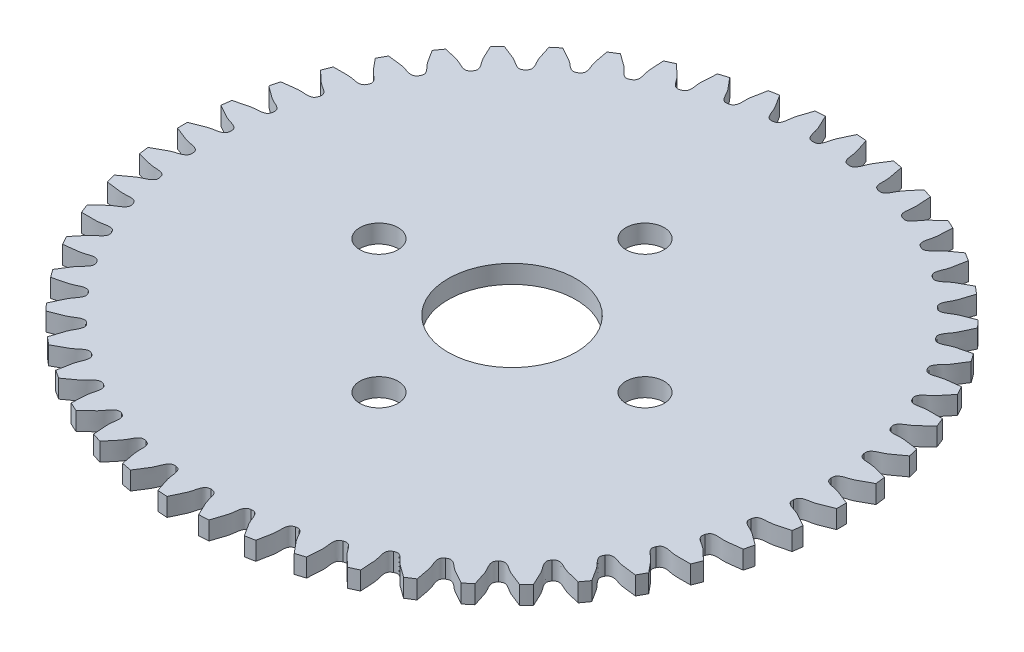
SolidWorks part; units mm, degrees
ref_plane "Front" through (0, 0, 0) normal (0, 0, 1) x (1, 0, 0)
ref_plane "Top" through (0, 0, 0) normal (0, 1, 0) x (1, 0, 0)
ref_plane "Right" through (0, 0, 0) normal (1, 0, 0) x (0, 0, -1)
sketch "Sketch1" plane through (0, 0, 0) normal (0, 1, 0) x (1, 0, 0)
  arc A0 (-11.3167, -17.258) -> (-10.7971, -17.5878) centre (0, 0) ccw
  arc A1 (-13.3905, -15.7035) -> (-12.9163, -16.0959) centre (0, 0) ccw
  arc A2 (-15.2531, -13.9014) -> (-14.8318, -14.3501) centre (0, 0) ccw
  arc A3 (-16.8751, -11.8801) -> (-16.5133, -12.378) centre (0, 0) ccw
  arc A4 (-18.231, -9.6714) -> (-17.9345, -10.2108) centre (0, 0) ccw
  arc A5 (-19.2994, -7.3102) -> (-19.0728, -7.8825) centre (0, 0) ccw
  arc A7 (-20.0634, -4.8337) -> (-19.9104, -5.4298) centre (0, 0) ccw
  arc A8 (-20.5111, -2.281) -> (-20.4339, -2.8916) centre (0, 0) ccw
  arc A9 (-20.6352, 0.3077) -> (-20.6352, -0.3077) centre (0, 0) ccw
  arc A10 (-20.4339, 2.8916) -> (-20.5111, 2.281) centre (0, 0) ccw
  arc A11 (-19.9104, 5.4298) -> (-20.0634, 4.8337) centre (0, 0) ccw
  arc A12 (-19.0728, 7.8825) -> (-19.2994, 7.3102) centre (0, 0) ccw
  arc A13 (-17.9345, 10.2108) -> (-18.231, 9.6714) centre (0, 0) ccw
  arc A14 (-16.5133, 12.378) -> (-16.8751, 11.8801) centre (0, 0) ccw
  arc A15 (-14.8318, 14.3501) -> (-15.2531, 13.9014) centre (0, 0) ccw
  arc A16 (-12.9163, 16.0959) -> (-13.3905, 15.7035) centre (0, 0) ccw
  arc A17 (-10.7971, 17.5878) -> (-11.3167, 17.258) centre (0, 0) ccw
  arc A18 (-8.5076, 18.8023) -> (-9.0645, 18.5403) centre (0, 0) ccw
  arc A19 (-6.084, 19.7203) -> (-6.6693, 19.5302) centre (0, 0) ccw
  arc A20 (-3.5644, 20.3274) -> (-4.1689, 20.212) centre (0, 0) ccw
  arc A21 (-0.9886, 20.6138) -> (-1.6028, 20.5752) centre (0, 0) ccw
  arc A22 (1.6028, 20.5752) -> (0.9886, 20.6138) centre (0, 0) ccw
  arc A23 (4.1689, 20.212) -> (3.5644, 20.3274) centre (0, 0) ccw
  arc A24 (6.6693, 19.5302) -> (6.084, 19.7203) centre (0, 0) ccw
  arc A25 (9.0645, 18.5403) -> (8.5076, 18.8023) centre (0, 0) ccw
  arc A26 (11.3167, 17.258) -> (10.7971, 17.5878) centre (0, 0) ccw
  arc A27 (13.3905, 15.7035) -> (12.9163, 16.0959) centre (0, 0) ccw
  arc A28 (15.2531, 13.9014) -> (14.8318, 14.3501) centre (0, 0) ccw
  arc A29 (16.8751, 11.8801) -> (16.5133, 12.378) centre (0, 0) ccw
  arc A30 (18.231, 9.6714) -> (17.9345, 10.2108) centre (0, 0) ccw
  arc A31 (19.2994, 7.3102) -> (19.0728, 7.8825) centre (0, 0) ccw
  arc A32 (20.0634, 4.8337) -> (19.9104, 5.4298) centre (0, 0) ccw
  arc A33 (20.5111, 2.281) -> (20.4339, 2.8916) centre (0, 0) ccw
  arc A34 (20.6352, -0.3077) -> (20.6352, 0.3077) centre (0, 0) ccw
  arc A35 (20.4339, -2.8916) -> (20.5111, -2.281) centre (0, 0) ccw
  arc A36 (-9.0645, -18.5403) -> (-8.5076, -18.8023) centre (0, 0) ccw
  arc A37 (19.9104, -5.4298) -> (20.0634, -4.8337) centre (0, 0) ccw
  arc A38 (19.0728, -7.8825) -> (19.2994, -7.3102) centre (0, 0) ccw
  arc A39 (17.9345, -10.2108) -> (18.231, -9.6714) centre (0, 0) ccw
  arc A40 (16.5133, -12.378) -> (16.8751, -11.8801) centre (0, 0) ccw
  arc A41 (14.8318, -14.3501) -> (15.2531, -13.9014) centre (0, 0) ccw
  arc A42 (12.9163, -16.0959) -> (13.3905, -15.7035) centre (0, 0) ccw
  arc A43 (10.7971, -17.5878) -> (11.3167, -17.258) centre (0, 0) ccw
  arc A44 (8.5076, -18.8023) -> (9.0645, -18.5403) centre (0, 0) ccw
  arc A45 (6.084, -19.7203) -> (6.6693, -19.5302) centre (0, 0) ccw
  arc A46 (3.5644, -20.3274) -> (4.1689, -20.212) centre (0, 0) ccw
  arc A47 (0.9886, -20.6138) -> (1.6028, -20.5752) centre (0, 0) ccw
  arc A48 (-1.6028, -20.5752) -> (-0.9886, -20.6138) centre (0, 0) ccw
  arc A49 (-4.1689, -20.212) -> (-3.5644, -20.3274) centre (0, 0) ccw
  arc A50 (-6.6693, -19.5302) -> (-6.084, -19.7203) centre (0, 0) ccw
  circle A51 centre (0, 0) radius 4
  circle A52 centre (-8.331, 0) radius 1.2
  circle A53 centre (0, 8.331) radius 1.2
  circle A54 centre (8.331, 0) radius 1.2
  circle A55 centre (0, -8.331) radius 1.2
  spline S0 degree 3 poles (-10.7971, -17.5878) (-10.6686, -17.4999) (-10.3251, -17.2651) (-9.873, -16.9278) (-9.5768, -16.5504) (-9.2878, -16.4134) (-9.1437, -16.4793) (-9.0765, -16.51) knots 0 0 0 0 0.220154 0.588354 0.785743 0.900027 1 1 1 1
  spline S1 degree 3 poles (-11.3167, -17.258) (-11.2919, -17.1043) (-11.2257, -16.6936) (-11.113, -16.1408) (-10.8977, -15.7122) (-10.8967, -15.3923) (-11.0177, -15.29) (-11.0741, -15.2422) knots 0 0 0 0 0.220154 0.588354 0.785743 0.900027 1 1 1 1
  spline S2 degree 3 poles (-12.9163, -16.0959) (-12.7778, -16.0248) (-12.4076, -15.8349) (-11.9168, -15.5569) (-11.5756, -15.2196) (-11.2717, -15.1199) (-11.137, -15.2033) (-11.0741, -15.2422) knots 0 0 0 0 0.220154 0.588354 0.785743 0.900027 1 1 1 1
  spline S3 degree 3 poles (-13.3905, -15.7035) (-13.3466, -15.5542) (-13.2294, -15.155) (-13.0483, -14.6207) (-12.781, -14.2224) (-12.74, -13.9052) (-12.8472, -13.7885) (-12.8972, -13.7341) knots 0 0 0 0 0.220154 0.588354 0.785743 0.900027 1 1 1 1
  spline S4 degree 3 poles (-14.8318, -14.3501) (-14.6854, -14.297) (-14.2944, -14.1549) (-13.7726, -13.9406) (-13.3918, -13.6488) (-13.0779, -13.5879) (-12.9547, -13.6876) (-12.8972, -13.7341) knots 0 0 0 0 0.220154 0.588354 0.785743 0.900027 1 1 1 1
  spline S5 degree 3 poles (-15.2531, -13.9014) (-15.1909, -13.7587) (-15.0246, -13.3774) (-14.7779, -12.8701) (-14.4627, -12.5084) (-14.3823, -12.1989) (-14.474, -12.0696) (-14.5168, -12.0094) knots 0 0 0 0 0.220154 0.588354 0.785743 0.900027 1 1 1 1
  spline S6 degree 3 poles (-16.5133, -12.378) (-16.3615, -12.3436) (-15.9558, -12.2517) (-15.4112, -12.1045) (-14.9969, -11.8627) (-14.6778, -11.8417) (-14.568, -11.956) (-14.5168, -12.0094) knots 0 0 0 0 0.220154 0.588354 0.785743 0.900027 1 1 1 1
  spline S7 degree 3 poles (-16.8751, -11.8801) (-16.7955, -11.7463) (-16.5827, -11.3889) (-16.2744, -10.9164) (-15.9164, -10.5971) (-15.7978, -10.3001) (-15.8726, -10.1604) (-15.9075, -10.0952) knots 0 0 0 0 0.220154 0.588354 0.785743 0.900027 1 1 1 1
  spline S8 degree 3 poles (-17.9345, -10.2108) (-17.7796, -10.1957) (-17.3655, -10.1553) (-16.8068, -10.0776) (-16.3654, -9.8896) (-16.0462, -9.9087) (-15.9516, -10.0359) (-15.9075, -10.0952) knots 0 0 0 0 0.220154 0.588354 0.785743 0.900027 1 1 1 1
  spline S9 degree 3 poles (-18.231, -9.6714) (-18.1353, -9.5487) (-17.8794, -9.2207) (-17.5143, -8.7906) (-17.1191, -8.5187) (-16.9642, -8.2389) (-17.0209, -8.0909) (-17.0473, -8.0219) knots 0 0 0 0 0.220154 0.588354 0.785743 0.900027 1 1 1 1
  spline S10 degree 3 poles (-19.0728, -7.8825) (-18.9172, -7.8869) (-18.5014, -7.8988) (-17.9373, -7.8916) (-17.4759, -7.7605) (-17.1615, -7.8195) (-17.0837, -7.9575) (-17.0473, -8.0219) knots 0 0 0 0 0.220154 0.588354 0.785743 0.900027 1 1 1 1
  spline S11 degree 3 poles (-19.2994, -7.3102) (-19.189, -7.2004) (-18.894, -6.9071) (-18.4779, -6.5262) (-18.0518, -6.3059) (-17.863, -6.0477) (-17.9007, -5.8938) (-17.9183, -5.822) knots 0 0 0 0 0.220154 0.588354 0.785743 0.900027 1 1 1 1
  spline S12 degree 3 poles (-19.9104, -5.4298) (-19.7566, -5.4538) (-19.3455, -5.5177) (-18.785, -5.5813) (-18.3107, -5.509) (-18.0062, -5.6069) (-17.9463, -5.7536) (-17.9183, -5.822) knots 0 0 0 0 0.220154 0.588354 0.785743 0.900027 1 1 1 1
  spline S13 degree 3 poles (-20.0634, -4.8337) (-19.9402, -4.7386) (-19.6107, -4.4846) (-19.1502, -4.1588) (-18.6998, -3.9937) (-18.4801, -3.7612) (-18.4983, -3.6038) (-18.5067, -3.5303) knots 0 0 0 0 0.220154 0.588354 0.785743 0.900027 1 1 1 1
  spline S14 degree 3 poles (-20.4339, -2.8916) (-20.2843, -2.9346) (-19.8845, -3.0495) (-19.3364, -3.1829) (-18.8568, -3.1706) (-18.567, -3.3059) (-18.5259, -3.4589) (-18.5067, -3.5303) knots 0 0 0 0 0.220154 0.588354 0.785743 0.900027 1 1 1 1
  spline S15 degree 3 poles (-20.5111, -2.281) (-20.3768, -2.2021) (-20.0182, -1.9913) (-19.5204, -1.7259) (-19.0529, -1.6185) (-18.8058, -1.4154) (-18.8041, -1.2569) (-18.8033, -1.183) knots 0 0 0 0 0.220154 0.588354 0.785743 0.900027 1 1 1 1
  spline S16 degree 3 poles (-20.6352, -0.3077) (-20.4922, -0.3692) (-20.1099, -0.5333) (-19.5828, -0.7343) (-19.1055, -0.7822) (-18.8349, -0.9528) (-18.8133, -1.1098) (-18.8033, -1.183) knots 0 0 0 0 0.220154 0.588354 0.785743 0.900027 1 1 1 1
  spline S17 degree 3 poles (-20.6352, 0.3077) (-20.4922, 0.3692) (-20.1099, 0.5333) (-19.5828, 0.7343) (-19.1055, 0.7822) (-18.8349, 0.9528) (-18.8133, 1.1098) (-18.8033, 1.183) knots 0 0 0 0 0.220154 0.588354 0.785743 0.900027 1 1 1 1
  spline S18 degree 3 poles (-20.5111, 2.281) (-20.3768, 2.2021) (-20.0182, 1.9913) (-19.5204, 1.7259) (-19.0529, 1.6185) (-18.8058, 1.4154) (-18.8041, 1.2569) (-18.8033, 1.183) knots 0 0 0 0 0.220154 0.588354 0.785743 0.900027 1 1 1 1
  spline S19 degree 3 poles (-20.4339, 2.8916) (-20.2843, 2.9346) (-19.8845, 3.0495) (-19.3364, 3.1829) (-18.8568, 3.1706) (-18.567, 3.3059) (-18.5259, 3.4589) (-18.5067, 3.5303) knots 0 0 0 0 0.220154 0.588354 0.785743 0.900027 1 1 1 1
  spline S20 degree 3 poles (-20.0634, 4.8337) (-19.9402, 4.7386) (-19.6107, 4.4846) (-19.1502, 4.1588) (-18.6998, 3.9937) (-18.4801, 3.7612) (-18.4983, 3.6038) (-18.5067, 3.5303) knots 0 0 0 0 0.220154 0.588354 0.785743 0.900027 1 1 1 1
  spline S21 degree 3 poles (-19.9104, 5.4298) (-19.7566, 5.4538) (-19.3455, 5.5177) (-18.785, 5.5813) (-18.3107, 5.509) (-18.0062, 5.6069) (-17.9463, 5.7536) (-17.9183, 5.822) knots 0 0 0 0 0.220154 0.588354 0.785743 0.900027 1 1 1 1
  spline S22 degree 3 poles (-19.2994, 7.3102) (-19.189, 7.2004) (-18.894, 6.9071) (-18.4779, 6.5262) (-18.0518, 6.3059) (-17.863, 6.0477) (-17.9007, 5.8938) (-17.9183, 5.822) knots 0 0 0 0 0.220154 0.588354 0.785743 0.900027 1 1 1 1
  spline S23 degree 3 poles (-19.0728, 7.8825) (-18.9172, 7.8869) (-18.5014, 7.8988) (-17.9373, 7.8916) (-17.4759, 7.7605) (-17.1615, 7.8195) (-17.0837, 7.9575) (-17.0473, 8.0219) knots 0 0 0 0 0.220154 0.588354 0.785743 0.900027 1 1 1 1
  spline S24 degree 3 poles (-18.231, 9.6714) (-18.1353, 9.5487) (-17.8794, 9.2207) (-17.5143, 8.7906) (-17.1191, 8.5187) (-16.9642, 8.2389) (-17.0209, 8.0909) (-17.0473, 8.0219) knots 0 0 0 0 0.220154 0.588354 0.785743 0.900027 1 1 1 1
  spline S25 degree 3 poles (-17.9345, 10.2108) (-17.7796, 10.1957) (-17.3655, 10.1553) (-16.8068, 10.0776) (-16.3654, 9.8896) (-16.0462, 9.9087) (-15.9516, 10.0359) (-15.9075, 10.0952) knots 0 0 0 0 0.220154 0.588354 0.785743 0.900027 1 1 1 1
  spline S26 degree 3 poles (-16.8751, 11.8801) (-16.7955, 11.7463) (-16.5827, 11.3889) (-16.2744, 10.9164) (-15.9164, 10.5971) (-15.7978, 10.3001) (-15.8726, 10.1604) (-15.9075, 10.0952) knots 0 0 0 0 0.220154 0.588354 0.785743 0.900027 1 1 1 1
  spline S27 degree 3 poles (-16.5133, 12.378) (-16.3615, 12.3436) (-15.9558, 12.2517) (-15.4112, 12.1045) (-14.9969, 11.8627) (-14.6778, 11.8417) (-14.568, 11.956) (-14.5168, 12.0094) knots 0 0 0 0 0.220154 0.588354 0.785743 0.900027 1 1 1 1
  spline S28 degree 3 poles (-15.2531, 13.9014) (-15.1909, 13.7587) (-15.0246, 13.3774) (-14.7779, 12.8701) (-14.4627, 12.5084) (-14.3823, 12.1989) (-14.474, 12.0696) (-14.5168, 12.0094) knots 0 0 0 0 0.220154 0.588354 0.785743 0.900027 1 1 1 1
  spline S29 degree 3 poles (-14.8318, 14.3501) (-14.6854, 14.297) (-14.2944, 14.1549) (-13.7726, 13.9406) (-13.3918, 13.6488) (-13.0779, 13.5879) (-12.9547, 13.6876) (-12.8972, 13.7341) knots 0 0 0 0 0.220154 0.588354 0.785743 0.900027 1 1 1 1
  spline S30 degree 3 poles (-13.3905, 15.7035) (-13.3466, 15.5542) (-13.2294, 15.155) (-13.0483, 14.6207) (-12.781, 14.2224) (-12.74, 13.9052) (-12.8472, 13.7885) (-12.8972, 13.7341) knots 0 0 0 0 0.220154 0.588354 0.785743 0.900027 1 1 1 1
  spline S31 degree 3 poles (-12.9163, 16.0959) (-12.7778, 16.0248) (-12.4076, 15.8349) (-11.9168, 15.5569) (-11.5756, 15.2196) (-11.2717, 15.1199) (-11.137, 15.2033) (-11.0741, 15.2422) knots 0 0 0 0 0.220154 0.588354 0.785743 0.900027 1 1 1 1
  spline S32 degree 3 poles (-11.3167, 17.258) (-11.2919, 17.1043) (-11.2257, 16.6936) (-11.113, 16.1408) (-10.8977, 15.7122) (-10.8967, 15.3923) (-11.0177, 15.29) (-11.0741, 15.2422) knots 0 0 0 0 0.220154 0.588354 0.785743 0.900027 1 1 1 1
  spline S33 degree 3 poles (-10.7971, 17.5878) (-10.6686, 17.4999) (-10.3251, 17.2651) (-9.873, 16.9278) (-9.5768, 16.5504) (-9.2878, 16.4134) (-9.1437, 16.4793) (-9.0765, 16.51) knots 0 0 0 0 0.220154 0.588354 0.785743 0.900027 1 1 1 1
  spline S34 degree 3 poles (-9.0645, 18.5403) (-9.0592, 18.3847) (-9.0449, 17.9689) (-9.0024, 17.4064) (-8.8425, 16.9541) (-8.8816, 16.6367) (-9.0145, 16.5503) (-9.0765, 16.51) knots 0 0 0 0 0.220154 0.588354 0.785743 0.900027 1 1 1 1
  spline S35 degree 3 poles (-8.5076, 18.8023) (-8.3911, 18.699) (-8.0798, 18.423) (-7.6735, 18.0317) (-7.4269, 17.6202) (-7.1574, 17.448) (-7.0062, 17.4953) (-6.9356, 17.5174) knots 0 0 0 0 0.220154 0.588354 0.785743 0.900027 1 1 1 1
  spline S36 degree 3 poles (-6.6693, 19.5302) (-6.6835, 19.3751) (-6.7215, 18.9609) (-6.7498, 18.3974) (-6.6478, 17.9287) (-6.7265, 17.6187) (-6.8691, 17.5496) (-6.9356, 17.5174) knots 0 0 0 0 0.220154 0.588354 0.785743 0.900027 1 1 1 1
  spline S37 degree 3 poles (-6.084, 19.7203) (-5.9813, 19.6033) (-5.7071, 19.2904) (-5.3531, 18.8513) (-5.16, 18.4121) (-4.9142, 18.2075) (-4.7582, 18.2355) (-4.6854, 18.2485) knots 0 0 0 0 0.220154 0.588354 0.785743 0.900027 1 1 1 1
  spline S38 degree 3 poles (-4.1689, 20.212) (-4.2025, 20.06) (-4.2921, 19.6538) (-4.3907, 19.0983) (-4.3484, 18.6205) (-4.4652, 18.3228) (-4.6154, 18.2722) (-4.6854, 18.2485) knots 0 0 0 0 0.220154 0.588354 0.785743 0.900027 1 1 1 1
  spline S39 degree 3 poles (-3.5644, 20.3274) (-3.4772, 20.1984) (-3.2444, 19.8536) (-2.9482, 19.3735) (-2.8117, 18.9136) (-2.5934, 18.6798) (-2.4352, 18.6881) (-2.3613, 18.6919) knots 0 0 0 0 0.220154 0.588354 0.785743 0.900027 1 1 1 1
  spline S40 degree 3 poles (-1.6028, 20.5752) (-1.6551, 20.4285) (-1.795, 20.0367) (-1.9625, 19.4981) (-1.9803, 19.0187) (-2.1335, 18.7379) (-2.2889, 18.7065) (-2.3613, 18.6919) knots 0 0 0 0 0.220154 0.588354 0.785743 0.900027 1 1 1 1
  spline S41 degree 3 poles (-0.9886, 20.6138) (-0.9183, 20.4749) (-0.7305, 20.1037) (-0.4968, 19.5903) (-0.419, 19.1169) (-0.2318, 18.8576) (-0.0737, 18.8459) (0, 18.8405) knots 0 0 0 0 0.220154 0.588354 0.785743 0.900027 1 1 1 1
  spline S42 degree 3 poles (0.9886, 20.6138) (0.9183, 20.4749) (0.7305, 20.1037) (0.4968, 19.5903) (0.419, 19.1169) (0.2318, 18.8576) (0.0737, 18.8459) (0, 18.8405) knots 0 0 0 0 0.220154 0.588354 0.785743 0.900027 1 1 1 1
  spline S43 degree 3 poles (1.6028, 20.5752) (1.6551, 20.4285) (1.795, 20.0367) (1.9625, 19.4981) (1.9803, 19.0187) (2.1335, 18.7379) (2.2889, 18.7065) (2.3613, 18.6919) knots 0 0 0 0 0.220154 0.588354 0.785743 0.900027 1 1 1 1
  spline S44 degree 3 poles (3.5644, 20.3274) (3.4772, 20.1984) (3.2444, 19.8536) (2.9482, 19.3735) (2.8117, 18.9136) (2.5934, 18.6798) (2.4352, 18.6881) (2.3613, 18.6919) knots 0 0 0 0 0.220154 0.588354 0.785743 0.900027 1 1 1 1
  spline S45 degree 3 poles (4.1689, 20.212) (4.2025, 20.06) (4.2921, 19.6538) (4.3907, 19.0983) (4.3484, 18.6205) (4.4652, 18.3228) (4.6154, 18.2722) (4.6854, 18.2485) knots 0 0 0 0 0.220154 0.588354 0.785743 0.900027 1 1 1 1
  spline S46 degree 3 poles (6.084, 19.7203) (5.9813, 19.6033) (5.7071, 19.2904) (5.3531, 18.8513) (5.16, 18.4121) (4.9142, 18.2075) (4.7582, 18.2355) (4.6854, 18.2485) knots 0 0 0 0 0.220154 0.588354 0.785743 0.900027 1 1 1 1
  spline S47 degree 3 poles (6.6693, 19.5302) (6.6835, 19.3751) (6.7215, 18.9609) (6.7498, 18.3974) (6.6478, 17.9287) (6.7265, 17.6187) (6.8691, 17.5496) (6.9356, 17.5174) knots 0 0 0 0 0.220154 0.588354 0.785743 0.900027 1 1 1 1
  spline S48 degree 3 poles (8.5076, 18.8023) (8.3911, 18.699) (8.0798, 18.423) (7.6735, 18.0317) (7.4269, 17.6202) (7.1574, 17.448) (7.0062, 17.4953) (6.9356, 17.5174) knots 0 0 0 0 0.220154 0.588354 0.785743 0.900027 1 1 1 1
  spline S49 degree 3 poles (9.0645, 18.5403) (9.0592, 18.3847) (9.0449, 17.9689) (9.0024, 17.4064) (8.8425, 16.9541) (8.8816, 16.6367) (9.0145, 16.5503) (9.0765, 16.51) knots 0 0 0 0 0.220154 0.588354 0.785743 0.900027 1 1 1 1
  spline S50 degree 3 poles (10.7971, 17.5878) (10.6686, 17.4999) (10.3251, 17.2651) (9.873, 16.9278) (9.5768, 16.5504) (9.2878, 16.4134) (9.1437, 16.4793) (9.0765, 16.51) knots 0 0 0 0 0.220154 0.588354 0.785743 0.900027 1 1 1 1
  spline S51 degree 3 poles (11.3167, 17.258) (11.2919, 17.1043) (11.2257, 16.6936) (11.113, 16.1408) (10.8977, 15.7122) (10.8967, 15.3923) (11.0177, 15.29) (11.0741, 15.2422) knots 0 0 0 0 0.220154 0.588354 0.785743 0.900027 1 1 1 1
  spline S52 degree 3 poles (12.9163, 16.0959) (12.7778, 16.0248) (12.4076, 15.8349) (11.9168, 15.5569) (11.5756, 15.2196) (11.2717, 15.1199) (11.137, 15.2033) (11.0741, 15.2422) knots 0 0 0 0 0.220154 0.588354 0.785743 0.900027 1 1 1 1
  spline S53 degree 3 poles (13.3905, 15.7035) (13.3466, 15.5542) (13.2294, 15.155) (13.0483, 14.6207) (12.781, 14.2224) (12.74, 13.9052) (12.8472, 13.7885) (12.8972, 13.7341) knots 0 0 0 0 0.220154 0.588354 0.785743 0.900027 1 1 1 1
  spline S54 degree 3 poles (14.8318, 14.3501) (14.6854, 14.297) (14.2944, 14.1549) (13.7726, 13.9406) (13.3918, 13.6488) (13.0779, 13.5879) (12.9547, 13.6876) (12.8972, 13.7341) knots 0 0 0 0 0.220154 0.588354 0.785743 0.900027 1 1 1 1
  spline S55 degree 3 poles (15.2531, 13.9014) (15.1909, 13.7587) (15.0246, 13.3774) (14.7779, 12.8701) (14.4627, 12.5084) (14.3823, 12.1989) (14.474, 12.0696) (14.5168, 12.0094) knots 0 0 0 0 0.220154 0.588354 0.785743 0.900027 1 1 1 1
  spline S56 degree 3 poles (16.5133, 12.378) (16.3615, 12.3436) (15.9558, 12.2517) (15.4112, 12.1045) (14.9969, 11.8627) (14.6778, 11.8417) (14.568, 11.956) (14.5168, 12.0094) knots 0 0 0 0 0.220154 0.588354 0.785743 0.900027 1 1 1 1
  spline S57 degree 3 poles (16.8751, 11.8801) (16.7955, 11.7463) (16.5827, 11.3889) (16.2744, 10.9164) (15.9164, 10.5971) (15.7978, 10.3001) (15.8726, 10.1604) (15.9075, 10.0952) knots 0 0 0 0 0.220154 0.588354 0.785743 0.900027 1 1 1 1
  spline S58 degree 3 poles (17.9345, 10.2108) (17.7796, 10.1957) (17.3655, 10.1553) (16.8068, 10.0776) (16.3654, 9.8896) (16.0462, 9.9087) (15.9516, 10.0359) (15.9075, 10.0952) knots 0 0 0 0 0.220154 0.588354 0.785743 0.900027 1 1 1 1
  spline S59 degree 3 poles (18.231, 9.6714) (18.1353, 9.5487) (17.8794, 9.2207) (17.5143, 8.7906) (17.1191, 8.5187) (16.9642, 8.2389) (17.0209, 8.0909) (17.0473, 8.0219) knots 0 0 0 0 0.220154 0.588354 0.785743 0.900027 1 1 1 1
  spline S60 degree 3 poles (19.0728, 7.8825) (18.9172, 7.8869) (18.5014, 7.8988) (17.9373, 7.8916) (17.4759, 7.7605) (17.1615, 7.8195) (17.0837, 7.9575) (17.0473, 8.0219) knots 0 0 0 0 0.220154 0.588354 0.785743 0.900027 1 1 1 1
  spline S61 degree 3 poles (19.2994, 7.3102) (19.189, 7.2004) (18.894, 6.9071) (18.4779, 6.5262) (18.0518, 6.3059) (17.863, 6.0477) (17.9007, 5.8938) (17.9183, 5.822) knots 0 0 0 0 0.220154 0.588354 0.785743 0.900027 1 1 1 1
  spline S62 degree 3 poles (19.9104, 5.4298) (19.7566, 5.4538) (19.3455, 5.5177) (18.785, 5.5813) (18.3107, 5.509) (18.0062, 5.6069) (17.9463, 5.7536) (17.9183, 5.822) knots 0 0 0 0 0.220154 0.588354 0.785743 0.900027 1 1 1 1
  spline S63 degree 3 poles (20.0634, 4.8337) (19.9402, 4.7386) (19.6107, 4.4846) (19.1502, 4.1588) (18.6998, 3.9937) (18.4801, 3.7612) (18.4983, 3.6038) (18.5067, 3.5303) knots 0 0 0 0 0.220154 0.588354 0.785743 0.900027 1 1 1 1
  spline S64 degree 3 poles (-8.5076, -18.8023) (-8.3911, -18.699) (-8.0798, -18.423) (-7.6735, -18.0317) (-7.4269, -17.6202) (-7.1574, -17.448) (-7.0062, -17.4953) (-6.9356, -17.5174) knots 0 0 0 0 0.220154 0.588354 0.785743 0.900027 1 1 1 1
  spline S65 degree 3 poles (-9.0645, -18.5403) (-9.0592, -18.3847) (-9.0449, -17.9689) (-9.0024, -17.4064) (-8.8425, -16.9541) (-8.8816, -16.6367) (-9.0145, -16.5503) (-9.0765, -16.51) knots 0 0 0 0 0.220154 0.588354 0.785743 0.900027 1 1 1 1
  spline S66 degree 3 poles (20.4339, 2.8916) (20.2843, 2.9346) (19.8845, 3.0495) (19.3364, 3.1829) (18.8568, 3.1706) (18.567, 3.3059) (18.5259, 3.4589) (18.5067, 3.5303) knots 0 0 0 0 0.220154 0.588354 0.785743 0.900027 1 1 1 1
  spline S67 degree 3 poles (20.5111, 2.281) (20.3768, 2.2021) (20.0182, 1.9913) (19.5204, 1.7259) (19.0529, 1.6185) (18.8058, 1.4154) (18.8041, 1.2569) (18.8033, 1.183) knots 0 0 0 0 0.220154 0.588354 0.785743 0.900027 1 1 1 1
  spline S68 degree 3 poles (20.6352, 0.3077) (20.4922, 0.3692) (20.1099, 0.5333) (19.5828, 0.7343) (19.1055, 0.7822) (18.8349, 0.9528) (18.8133, 1.1098) (18.8033, 1.183) knots 0 0 0 0 0.220154 0.588354 0.785743 0.900027 1 1 1 1
  spline S69 degree 3 poles (20.6352, -0.3077) (20.4922, -0.3692) (20.1099, -0.5333) (19.5828, -0.7343) (19.1055, -0.7822) (18.8349, -0.9528) (18.8133, -1.1098) (18.8033, -1.183) knots 0 0 0 0 0.220154 0.588354 0.785743 0.900027 1 1 1 1
  spline S70 degree 3 poles (20.5111, -2.281) (20.3768, -2.2021) (20.0182, -1.9913) (19.5204, -1.7259) (19.0529, -1.6185) (18.8058, -1.4154) (18.8041, -1.2569) (18.8033, -1.183) knots 0 0 0 0 0.220154 0.588354 0.785743 0.900027 1 1 1 1
  spline S71 degree 3 poles (20.4339, -2.8916) (20.2843, -2.9346) (19.8845, -3.0495) (19.3364, -3.1829) (18.8568, -3.1706) (18.567, -3.3059) (18.5259, -3.4589) (18.5067, -3.5303) knots 0 0 0 0 0.220154 0.588354 0.785743 0.900027 1 1 1 1
  spline S72 degree 3 poles (20.0634, -4.8337) (19.9402, -4.7386) (19.6107, -4.4846) (19.1502, -4.1588) (18.6998, -3.9937) (18.4801, -3.7612) (18.4983, -3.6038) (18.5067, -3.5303) knots 0 0 0 0 0.220154 0.588354 0.785743 0.900027 1 1 1 1
  spline S73 degree 3 poles (19.9104, -5.4298) (19.7566, -5.4538) (19.3455, -5.5177) (18.785, -5.5813) (18.3107, -5.509) (18.0062, -5.6069) (17.9463, -5.7536) (17.9183, -5.822) knots 0 0 0 0 0.220154 0.588354 0.785743 0.900027 1 1 1 1
  spline S74 degree 3 poles (19.2994, -7.3102) (19.189, -7.2004) (18.894, -6.9071) (18.4779, -6.5262) (18.0518, -6.3059) (17.863, -6.0477) (17.9007, -5.8938) (17.9183, -5.822) knots 0 0 0 0 0.220154 0.588354 0.785743 0.900027 1 1 1 1
  spline S75 degree 3 poles (19.0728, -7.8825) (18.9172, -7.8869) (18.5014, -7.8988) (17.9373, -7.8916) (17.4759, -7.7605) (17.1615, -7.8195) (17.0837, -7.9575) (17.0473, -8.0219) knots 0 0 0 0 0.220154 0.588354 0.785743 0.900027 1 1 1 1
  spline S76 degree 3 poles (18.231, -9.6714) (18.1353, -9.5487) (17.8794, -9.2207) (17.5143, -8.7906) (17.1191, -8.5187) (16.9642, -8.2389) (17.0209, -8.0909) (17.0473, -8.0219) knots 0 0 0 0 0.220154 0.588354 0.785743 0.900027 1 1 1 1
  spline S77 degree 3 poles (17.9345, -10.2108) (17.7796, -10.1957) (17.3655, -10.1553) (16.8068, -10.0776) (16.3654, -9.8896) (16.0462, -9.9087) (15.9516, -10.0359) (15.9075, -10.0952) knots 0 0 0 0 0.220154 0.588354 0.785743 0.900027 1 1 1 1
  spline S78 degree 3 poles (16.8751, -11.8801) (16.7955, -11.7463) (16.5827, -11.3889) (16.2744, -10.9164) (15.9164, -10.5971) (15.7978, -10.3001) (15.8726, -10.1604) (15.9075, -10.0952) knots 0 0 0 0 0.220154 0.588354 0.785743 0.900027 1 1 1 1
  spline S79 degree 3 poles (16.5133, -12.378) (16.3615, -12.3436) (15.9558, -12.2517) (15.4112, -12.1045) (14.9969, -11.8627) (14.6778, -11.8417) (14.568, -11.956) (14.5168, -12.0094) knots 0 0 0 0 0.220154 0.588354 0.785743 0.900027 1 1 1 1
  spline S80 degree 3 poles (15.2531, -13.9014) (15.1909, -13.7587) (15.0246, -13.3774) (14.7779, -12.8701) (14.4627, -12.5084) (14.3823, -12.1989) (14.474, -12.0696) (14.5168, -12.0094) knots 0 0 0 0 0.220154 0.588354 0.785743 0.900027 1 1 1 1
  spline S81 degree 3 poles (14.8318, -14.3501) (14.6854, -14.297) (14.2944, -14.1549) (13.7726, -13.9406) (13.3918, -13.6488) (13.0779, -13.5879) (12.9547, -13.6876) (12.8972, -13.7341) knots 0 0 0 0 0.220154 0.588354 0.785743 0.900027 1 1 1 1
  spline S82 degree 3 poles (13.3905, -15.7035) (13.3466, -15.5542) (13.2294, -15.155) (13.0483, -14.6207) (12.781, -14.2224) (12.74, -13.9052) (12.8472, -13.7885) (12.8972, -13.7341) knots 0 0 0 0 0.220154 0.588354 0.785743 0.900027 1 1 1 1
  spline S83 degree 3 poles (12.9163, -16.0959) (12.7778, -16.0248) (12.4076, -15.8349) (11.9168, -15.5569) (11.5756, -15.2196) (11.2717, -15.1199) (11.137, -15.2033) (11.0741, -15.2422) knots 0 0 0 0 0.220154 0.588354 0.785743 0.900027 1 1 1 1
  spline S84 degree 3 poles (11.3167, -17.258) (11.2919, -17.1043) (11.2257, -16.6936) (11.113, -16.1408) (10.8977, -15.7122) (10.8967, -15.3923) (11.0177, -15.29) (11.0741, -15.2422) knots 0 0 0 0 0.220154 0.588354 0.785743 0.900027 1 1 1 1
  spline S85 degree 3 poles (10.7971, -17.5878) (10.6686, -17.4999) (10.3251, -17.2651) (9.873, -16.9278) (9.5768, -16.5504) (9.2878, -16.4134) (9.1437, -16.4793) (9.0765, -16.51) knots 0 0 0 0 0.220154 0.588354 0.785743 0.900027 1 1 1 1
  spline S86 degree 3 poles (9.0645, -18.5403) (9.0592, -18.3847) (9.0449, -17.9689) (9.0024, -17.4064) (8.8425, -16.9541) (8.8816, -16.6367) (9.0145, -16.5503) (9.0765, -16.51) knots 0 0 0 0 0.220154 0.588354 0.785743 0.900027 1 1 1 1
  spline S87 degree 3 poles (8.5076, -18.8023) (8.3911, -18.699) (8.0798, -18.423) (7.6735, -18.0317) (7.4269, -17.6202) (7.1574, -17.448) (7.0062, -17.4953) (6.9356, -17.5174) knots 0 0 0 0 0.220154 0.588354 0.785743 0.900027 1 1 1 1
  spline S88 degree 3 poles (6.6693, -19.5302) (6.6835, -19.3751) (6.7215, -18.9609) (6.7498, -18.3974) (6.6478, -17.9287) (6.7265, -17.6187) (6.8691, -17.5496) (6.9356, -17.5174) knots 0 0 0 0 0.220154 0.588354 0.785743 0.900027 1 1 1 1
  spline S89 degree 3 poles (6.084, -19.7203) (5.9813, -19.6033) (5.7071, -19.2904) (5.3531, -18.8513) (5.16, -18.4121) (4.9142, -18.2075) (4.7582, -18.2355) (4.6854, -18.2485) knots 0 0 0 0 0.220154 0.588354 0.785743 0.900027 1 1 1 1
  spline S90 degree 3 poles (4.1689, -20.212) (4.2025, -20.06) (4.2921, -19.6538) (4.3907, -19.0983) (4.3484, -18.6205) (4.4652, -18.3228) (4.6154, -18.2722) (4.6854, -18.2485) knots 0 0 0 0 0.220154 0.588354 0.785743 0.900027 1 1 1 1
  spline S91 degree 3 poles (3.5644, -20.3274) (3.4772, -20.1984) (3.2444, -19.8536) (2.9482, -19.3735) (2.8117, -18.9136) (2.5934, -18.6798) (2.4352, -18.6881) (2.3613, -18.6919) knots 0 0 0 0 0.220154 0.588354 0.785743 0.900027 1 1 1 1
  spline S92 degree 3 poles (1.6028, -20.5752) (1.6551, -20.4285) (1.795, -20.0367) (1.9625, -19.4981) (1.9803, -19.0187) (2.1335, -18.7379) (2.2889, -18.7065) (2.3613, -18.6919) knots 0 0 0 0 0.220154 0.588354 0.785743 0.900027 1 1 1 1
  spline S93 degree 3 poles (0.9886, -20.6138) (0.9183, -20.4749) (0.7305, -20.1037) (0.4968, -19.5903) (0.419, -19.1169) (0.2318, -18.8576) (0.0737, -18.8459) (0, -18.8405) knots 0 0 0 0 0.220154 0.588354 0.785743 0.900027 1 1 1 1
  spline S94 degree 3 poles (-0.9886, -20.6138) (-0.9183, -20.4749) (-0.7305, -20.1037) (-0.4968, -19.5903) (-0.419, -19.1169) (-0.2318, -18.8576) (-0.0737, -18.8459) (0, -18.8405) knots 0 0 0 0 0.220154 0.588354 0.785743 0.900027 1 1 1 1
  spline S95 degree 3 poles (-1.6028, -20.5752) (-1.6551, -20.4285) (-1.795, -20.0367) (-1.9625, -19.4981) (-1.9803, -19.0187) (-2.1335, -18.7379) (-2.2889, -18.7065) (-2.3613, -18.6919) knots 0 0 0 0 0.220154 0.588354 0.785743 0.900027 1 1 1 1
  spline S96 degree 3 poles (-3.5644, -20.3274) (-3.4772, -20.1984) (-3.2444, -19.8536) (-2.9482, -19.3735) (-2.8117, -18.9136) (-2.5934, -18.6798) (-2.4352, -18.6881) (-2.3613, -18.6919) knots 0 0 0 0 0.220154 0.588354 0.785743 0.900027 1 1 1 1
  spline S97 degree 3 poles (-4.1689, -20.212) (-4.2025, -20.06) (-4.2921, -19.6538) (-4.3907, -19.0983) (-4.3484, -18.6205) (-4.4652, -18.3228) (-4.6154, -18.2722) (-4.6854, -18.2485) knots 0 0 0 0 0.220154 0.588354 0.785743 0.900027 1 1 1 1
  spline S98 degree 3 poles (-6.084, -19.7203) (-5.9813, -19.6033) (-5.7071, -19.2904) (-5.3531, -18.8513) (-5.16, -18.4121) (-4.9142, -18.2075) (-4.7582, -18.2355) (-4.6854, -18.2485) knots 0 0 0 0 0.220154 0.588354 0.785743 0.900027 1 1 1 1
  spline S99 degree 3 poles (-6.6693, -19.5302) (-6.6835, -19.3751) (-6.7215, -18.9609) (-6.7498, -18.3974) (-6.6478, -17.9287) (-6.7265, -17.6187) (-6.8691, -17.5496) (-6.9356, -17.5174) knots 0 0 0 0 0.220154 0.588354 0.785743 0.900027 1 1 1 1
extrude "Extrude1" add sketch "Sketch1" along normal blind 1.143
